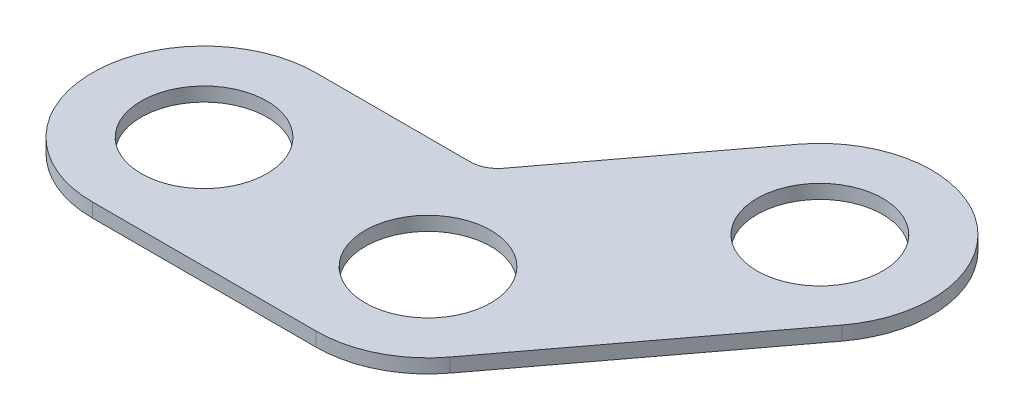
SolidWorks part; units mm, degrees
material "6061-T6 (SS)"
ref_plane "Front Plane" through (0, 0, 0) normal (0, 0, 1) x (1, 0, 0)
ref_plane "Top Plane" through (0, 0, 0) normal (0, 1, 0) x (1, 0, 0)
ref_plane "Right Plane" through (0, 0, 0) normal (1, 0, 0) x (0, 0, -1)
sketch "Sketch1" plane through (0, 0, 0) normal (0, 1, 0) x (1, 0, 0)
  line L0 (0, 0) -> (50.8762, 0) construction
  line L1 (0, 25.4) -> (38.2012, 25.4)
  line L2 (0, -25.4) -> (50.8762, -25.4)
  line L3 (50.8762, 0) -> (89.1019, 50.8009) construction
  line L4 (38.2012, 25.4) -> (68.8058, 66.0728)
  line L5 (71.1722, -15.2719) -> (109.3979, 35.529)
  arc A0 (0, 25.4) -> (0, -25.4) centre (0, 0) ccw
  arc A1 (50.8762, -25.4) -> (71.1722, -15.2719) centre (50.8762, 0) ccw
  arc A2 (50.8762, -25.4) -> (71.1722, -15.2719) centre (50.8762, 0) ccw
  arc A3 (109.3979, 35.529) -> (68.8058, 66.0728) centre (89.1019, 50.8009) ccw
  circle A4 centre (0, 0) radius 14.2875
  circle A5 centre (50.8762, 0) radius 14.2875
  circle A6 centre (89.1019, 50.8009) radius 14.2875
  point P3 (25.4381, 0)
  point P10 (69.989, 25.4005)
  dimension "D6" = 28.575
  dimension "D1" = 126.96
  dimension "D2" = 50.8
  dimension "D3" = 50.8762
  dimension "D4" = 50.8
  dimension "D5" = 63.5762
extrude "Boss-Extrude1" add sketch "Sketch1" along normal blind 3.175 contours L5 A3 L4 L1 A0 L2 A1 A6 A5 A4
fillet "Fillet2" radius 6.35 1 edges at (38.2012, 1.5875, -25.4)
